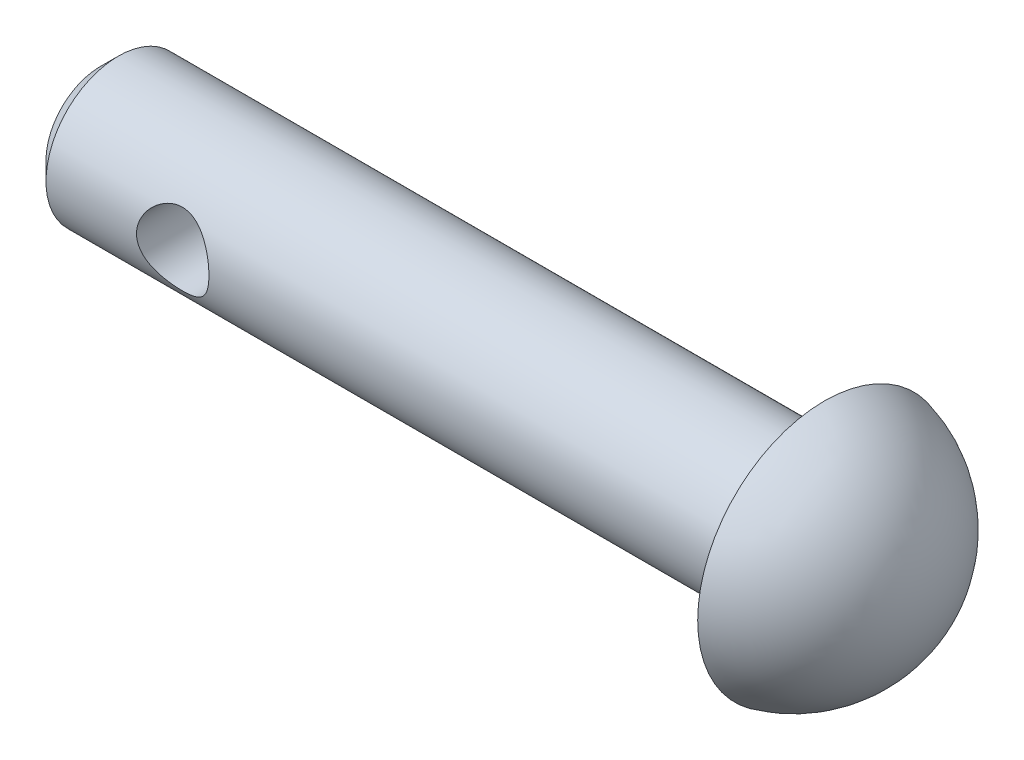
SolidWorks part; units mm, degrees
ref_plane "Front Plane" through (0, 0, 0) normal (0, 0, 1) x (1, 0, 0)
ref_plane "Top Plane" through (0, 0, 0) normal (0, 1, 0) x (1, 0, 0)
ref_plane "Right Plane" through (0, 0, 0) normal (1, 0, 0) x (0, 0, -1)
sketch "Sketch1" plane through (0, 0, 0) normal (1, 0, 0) x (0, 0, -1)
  circle A0 centre (0, 0) radius 2
  dimension "D1" = 4
extrude "Boss-Extrude1" add sketch "Sketch1" against normal blind 20
sketch "Sketch2" plane through (0, 0, 0) normal (0, 0, 1) x (1, 0, 0)
  circle A0 centre (-16, 0) radius 1
  point P2 (0, 0)
  dimension "D1" = 16
  dimension "D2" = 2
extrude "Cut-Extrude1" cut sketch "Sketch2" against normal through all both and the other way through all
chamfer "Chamfer1" distance 0.5 angle 45 1 edges at (-20, 0, -2)
sketch "Sketch3" plane through (0, 0, 0) normal (0, 1, 0) x (1, 0, 0)
  line L0 (-5.0901, 0) -> (3.914, 0) construction
  line L1 (0, 3.5) -> (0, 0)
  line L2 (0, 0) -> (2.7574, 0)
  arc A0 (0, 3.5) -> (2.7574, 0) centre (-0.8426, 0) cw
  point P7 (0, 0)
  dimension "D1" = 3.6
  dimension "D2" = 3.5
revolve "Revolve1" add sketch "Sketch3" angle 360 about L0
